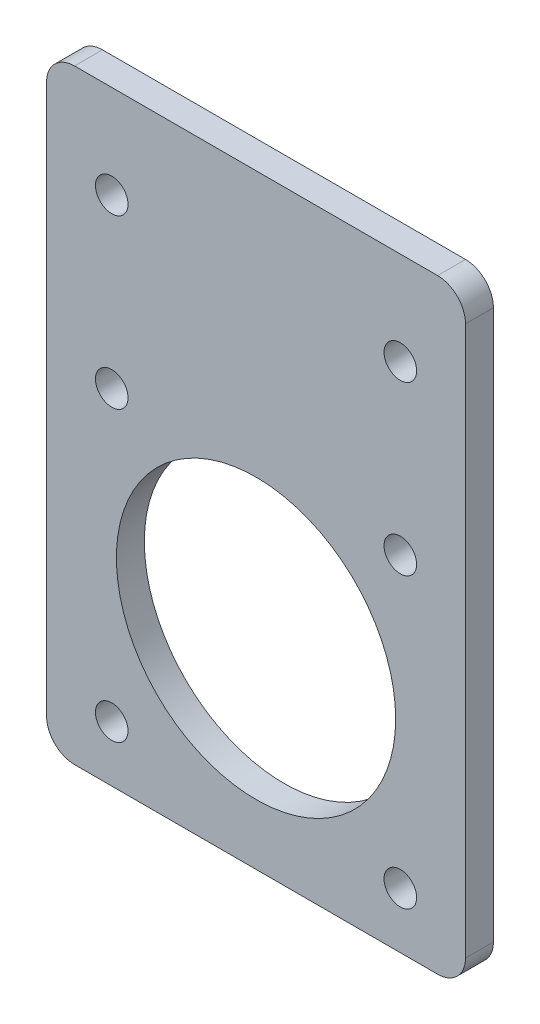
SolidWorks part; units mm, degrees
ref_plane "Ebene vorne" through (0, 0, 0) normal (0, 0, 1) x (1, 0, 0)
ref_plane "Ebene oben" through (0, 0, 0) normal (0, 1, 0) x (1, 0, 0)
ref_plane "Ebene rechts" through (0, 0, 0) normal (1, 0, 0) x (0, 0, -1)
sketch "Skizze1" plane through (0, 0, 0) normal (0, 0, 1) x (1, 0, 0)
  line L1 (22.5, 32.5) -> (-22.5, 32.5)
  line L2 (22.5, 32.5) -> (22.5, -32.5)
  line L3 (22.5, -32.5) -> (-22.5, -32.5)
  line L4 (-22.5, 32.5) -> (-22.5, -32.5)
  line L5 (22.5, 32.5) -> (-22.5, -32.5) construction
  line L6 (22.5, -32.5) -> (-22.5, 32.5) construction
  point P0 (0, 0)
  dimension "D1" = 65
  dimension "D2" = 45
extrude "Aufsatz-Linear austragen1" add sketch "Skizze1" along normal blind 3
fillet "Verrundung1" radius 3 4 edges at (-22.5, 32.5, 1.5) (22.5, 32.5, 1.5) (22.5, -32.5, 1.5) (-22.5, -32.5, 1.5)
sketch "Skizze2" plane through (0, 0, 3) normal (0, 0, 1) x (1, 0, 0)
  line L0 (-15.5, 22.5) -> (15.5, 22.5) construction
  line L1 (15.5, 4.5) -> (-15.5, 4.5) construction
  line L2 (15.5, 4.5) -> (15.5, -26.5) construction
  line L3 (15.5, -26.5) -> (-15.5, -26.5) construction
  line L4 (-15.5, 4.5) -> (-15.5, -26.5) construction
  line L5 (15.5, 4.5) -> (-15.5, -26.5) construction
  line L6 (15.5, -26.5) -> (-15.5, 4.5) construction
  line L8 (19.5, 32.5) -> (-19.5, 32.5) construction
  line L10 (-19.5, -32.5) -> (19.5, -32.5) construction
  line L11 (0, -11) -> (0, -32.5) construction
  line L12 (21.5, 10.5) -> (-21.5, 10.5) construction
  line L13 (21.5, 10.5) -> (21.5, -32.5) construction
  line L14 (21.5, -32.5) -> (-21.5, -32.5) construction
  line L15 (-21.5, 10.5) -> (-21.5, -32.5) construction
  line L16 (21.5, 10.5) -> (-21.5, -32.5) construction
  line L17 (21.5, -32.5) -> (-21.5, 10.5) construction
  circle A0 centre (-15.5, -26.5) radius 1.75
  circle A1 centre (-15.5, 4.5) radius 1.75
  circle A2 centre (15.5, 4.5) radius 1.75
  circle A3 centre (15.5, -26.5) radius 1.75
  circle A4 centre (15.5, 22.5) radius 1.75
  circle A5 centre (-15.5, 22.5) radius 1.75
  circle A6 centre (0, -11) radius 15
  point P0 (0, -11)
  point P15 (0, -11)
  dimension "D8" = 3.5
  dimension "D9" = 3.5
  dimension "D10" = 30
  dimension "D2" = 10
  dimension "D3" = 31
  dimension "D4" = 31
  dimension "D6" = 21.5
  dimension "D7" = 43
extrude "Schnitt-Linear austragen1" cut sketch "Skizze2" against normal blind 12
